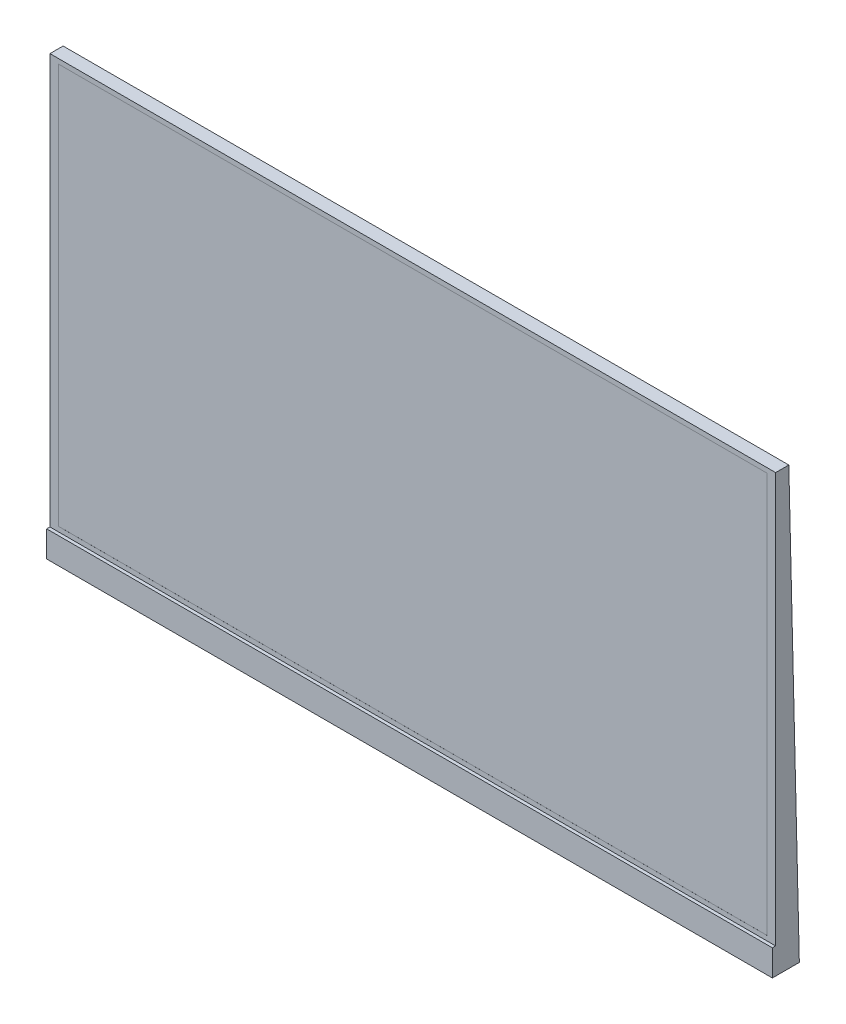
SolidWorks part; units mm, degrees
ref_plane "Front Plane" through (0, 0, 0) normal (0, 0, 1) x (1, 0, 0)
ref_plane "Top Plane" through (0, 0, 0) normal (0, 1, 0) x (1, 0, 0)
ref_plane "Right Plane" through (0, 0, 0) normal (1, 0, 0) x (0, 0, -1)
sketch "Sketch1" plane through (0, 0, 0) normal (0, 0, 1) x (1, 0, 0)
  line L1 (-269.4781, -161.925) -> (269.4781, -161.925)
  line L2 (-269.4781, -161.925) -> (-269.4781, 161.925)
  line L3 (-269.4781, 161.925) -> (269.4781, 161.925)
  line L4 (269.4781, -161.925) -> (269.4781, 161.925)
  line L5 (-269.4781, -161.925) -> (269.4781, 161.925) construction
  line L6 (-269.4781, 161.925) -> (269.4781, -161.925) construction
  point P0 (0, 0)
  dimension "D1" = 538.9563
  dimension "D2" = 323.85
extrude "Boss-Extrude1" add sketch "Sketch1" along normal blind 9.525
sketch "Sketch3" plane through (269.4781, 0, 0) normal (1, 0, 0) x (0, 0, -1)
  line L0 (-9.525, 161.925) -> (0.254, 161.925)
  line L1 (0.254, 161.925) -> (8.0625, -161.925)
  line L2 (-11.9527, -161.925) -> (-9.525, -161.925)
  line L3 (-11.9527, -161.925) -> (-11.9527, -142.5194)
  line L4 (-11.9527, -142.5194) -> (-9.525, -142.5194)
  line L5 (-9.525, -161.925) -> (-9.525, 161.925) construction
  line L6 (-9.525, -161.925) -> (0, -161.925)
  line L7 (0, -161.925) -> (8.0625, -161.925)
  line L8 (-9.525, -142.5194) -> (-9.525, 161.925)
  point P18 (7.5946, -142.5194)
  dimension "D1" = 9.779
  dimension "D2" = 20.0152
  dimension "D3" = 17.1196
  dimension "D4" = 19.4056
extrude "Boss-Extrude2" add sketch "Sketch3" against normal up to surface (538.9563 mm away) up to face at (-269.4781, 0, 4.7625)
sketch "Sketch4" plane through (269.4781, 0, 0) normal (1, 0, 0) x (0, 0, -1)
  line L0 (37.1936, 78.3717) -> (36.5763, -80.3771)
  line L3 (-9.525, 161.925) -> (0.254, 161.925) construction
  line L4 (8.0625, -161.925) -> (0.254, 161.925) construction
  line L5 (37.1936, 78.3717) -> (2.1914, 81.5712)
  line L6 (36.5763, -80.3771) -> (6.1576, -82.9192)
  line L13 (-11.9527, -161.925) -> (8.0625, -161.925)
  line L14 (8.0625, -161.925) -> (0.254, 161.925)
  line L15 (0.254, 161.925) -> (-9.525, 161.925)
  line L16 (-9.525, 161.925) -> (-9.525, -142.5194)
  line L17 (-9.525, -142.5194) -> (-11.9527, -142.5194)
  line L18 (-11.9527, -142.5194) -> (-11.9527, -161.925)
  line L20 (6.1576, -82.9192) -> (2.1914, 81.5712)
  point P2 (2.2686, 78.3717)
  point P6 (6.0963, -80.3771)
  dimension "D1" = 83.5533
  dimension "D2" = 158.75
  dimension "D3" = 34.925
  dimension "D4" = 30.48
  dimension "D5" = 95
  dimension "D6" = 95
  dimension "D7" = 0
extrude "Boss-Extrude3" add sketch "Sketch4" against normal up to surface (538.9563 mm away) up to face at (-269.4781, -47.5065, 5.7732)
sketch "Sketch5" plane through (0, 0.1002, -4.1558) normal (0, 0.0241, -0.9997) x (-1, 0, 0)
  line L0 (269.4781, 81.4947) -> (-269.4781, 81.4947) construction
  line L1 (-139.6841, 81.4947) -> (139.7159, 81.4947)
  line L2 (-139.6841, 81.4947) -> (-139.6841, -83.0436)
  line L3 (-139.6841, -83.0436) -> (139.7159, -83.0436)
  line L4 (139.7159, 81.4947) -> (139.7159, -83.0436)
  line L5 (269.4781, -83.0436) -> (-269.4781, -83.0436) construction
  line L6 (-269.4781, -81.2354) -> (-269.4781, 77.4524) construction
  line L7 (269.4781, -83.0436) -> (269.4781, -162.0723) construction
  line L8 (-139.6841, 81.4947) -> (-269.4781, 81.4947)
  line L9 (-139.6841, 81.4947) -> (-139.6841, -83.0436)
  line L10 (-139.6841, -83.0436) -> (-269.4781, -83.0436)
  line L11 (-269.4781, 81.4947) -> (-269.4781, -83.0436)
  line L12 (139.7159, 81.4947) -> (269.4781, 81.4947)
  line L13 (139.7159, 81.4947) -> (139.7159, -83.0436)
  line L14 (139.7159, -83.0436) -> (269.4781, -83.0436)
  line L15 (269.4781, 81.4947) -> (269.4781, -83.0436)
  line M3 (-269.4781, 81.4947) -> (269.4781, 81.4947)
  dimension "D1" = 279.4
  dimension "D2" = 129.794
extrude "Cut-Extrude1" cut sketch "Sketch5" along normal through all contours L11 L10 L2 M3 | L15 L4 L14 M3
fillet "Fillet1" radius 19.05 4 edges at (-139.7159, -0.674, -4.1745) (-0.0159, -82.9192, -6.1576) (139.6841, -0.674, -4.1745) (-0.0159, 81.5712, -2.1914)
sketch "Sketch6" plane through (0, 0, 9.525) normal (0, 0, 1) x (1, 0, 0)
  line L0 (-269.4781, 161.925) -> (-269.4781, -142.5194) construction
  line L1 (-263.1746, -138.9587) -> (263.1746, -138.9587)
  line L2 (-263.1746, -138.9587) -> (-263.1746, 158.3643)
  line L3 (-263.1746, 158.3643) -> (263.1746, 158.3643)
  line L4 (263.1746, -138.9587) -> (263.1746, 158.3643)
  line L5 (-263.1746, -138.9587) -> (263.1746, 158.3643) construction
  line L6 (-263.1746, 158.3643) -> (263.1746, -138.9587) construction
  line L7 (269.4781, 161.925) -> (-269.4781, 161.925) construction
  line L8 (269.4781, 161.925) -> (-269.4781, -142.5194) construction
  point P0 (0, 9.7028)
  point P7 (-269.4781, 9.7028)
  point P8 (0, 161.925)
  point P14 (0, 0)
  dimension "D1" = 604.52
extrude "Cut-Extrude2" cut sketch "Sketch6" against normal blind 0.0254
